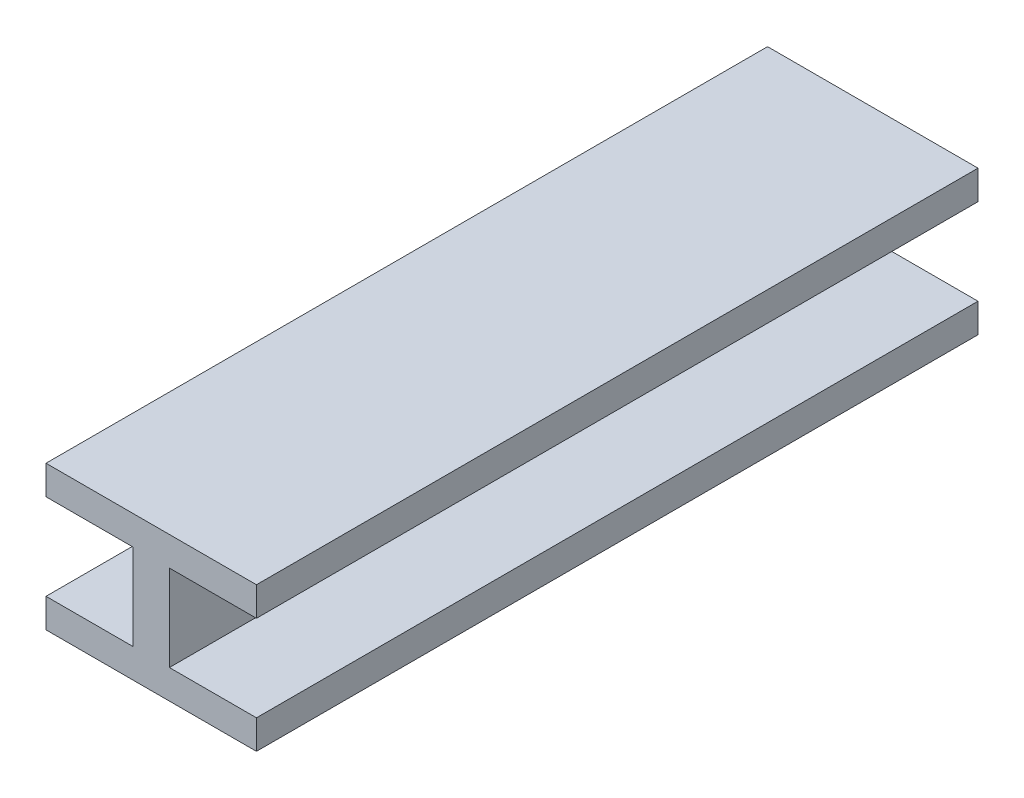
SolidWorks part; units mm, degrees
ref_plane "Front Plane" through (0, 0, 0) normal (0, 0, 1) x (1, 0, 0)
ref_plane "Top Plane" through (0, 0, 0) normal (0, 1, 0) x (1, 0, 0)
ref_plane "Right Plane" through (0, 0, 0) normal (1, 0, 0) x (0, 0, -1)
sketch "Sketch1" plane through (0, 0, 0) normal (0, 0, 1) x (1, 0, 0)
  line L0 (0, 50.8) -> (0, -50.8) construction
  line L1 (3.8372, 9.1005) -> (3.8372, -9.1005)
  line L2 (-3.8372, 9.1005) -> (-3.8372, -9.1005)
  line L3 (3.8372, -9.1005) -> (22.225, -9.1005)
  line L4 (-3.8372, -9.1005) -> (-22.225, -9.1005)
  line L5 (22.225, -9.1005) -> (22.225, -15.24)
  line L6 (-22.225, -9.1005) -> (-22.225, -15.24)
  line L7 (22.225, -15.24) -> (-22.225, -15.24)
  line L8 (-3.8372, 0) -> (3.8372, 0) construction
  line L9 (-22.225, 9.1005) -> (-22.225, 15.24)
  line L10 (-3.8372, 9.1005) -> (-22.225, 9.1005)
  line L11 (22.225, 15.24) -> (-22.225, 15.24)
  line L12 (22.225, 9.1005) -> (22.225, 15.24)
  line L13 (3.8372, 9.1005) -> (22.225, 9.1005)
  point P4 (0, 0)
  point P7 (3.8372, 0)
  point P13 (0, -15.24)
  point P17 (0, 0)
  dimension "D1" = 6.1395
  dimension "D2" = 30.48
  dimension "D3" = 7.6744
  dimension "D4" = 44.45
extrude "Boss-Extrude2" add sketch "Sketch1" along normal mid plane 152.4
equation "\"T\"= .2417125"
equation "\"H\"= 1.2"
equation "\"W\"= 1.75"
equation "\"D3@Sketch1\"=\"T\"*1.25"
equation "\"D1@Sketch1\"=\"T\""
equation "\"D4@Sketch1\"=\"W\""
equation "\"D2@Sketch1\"=\"H\""
